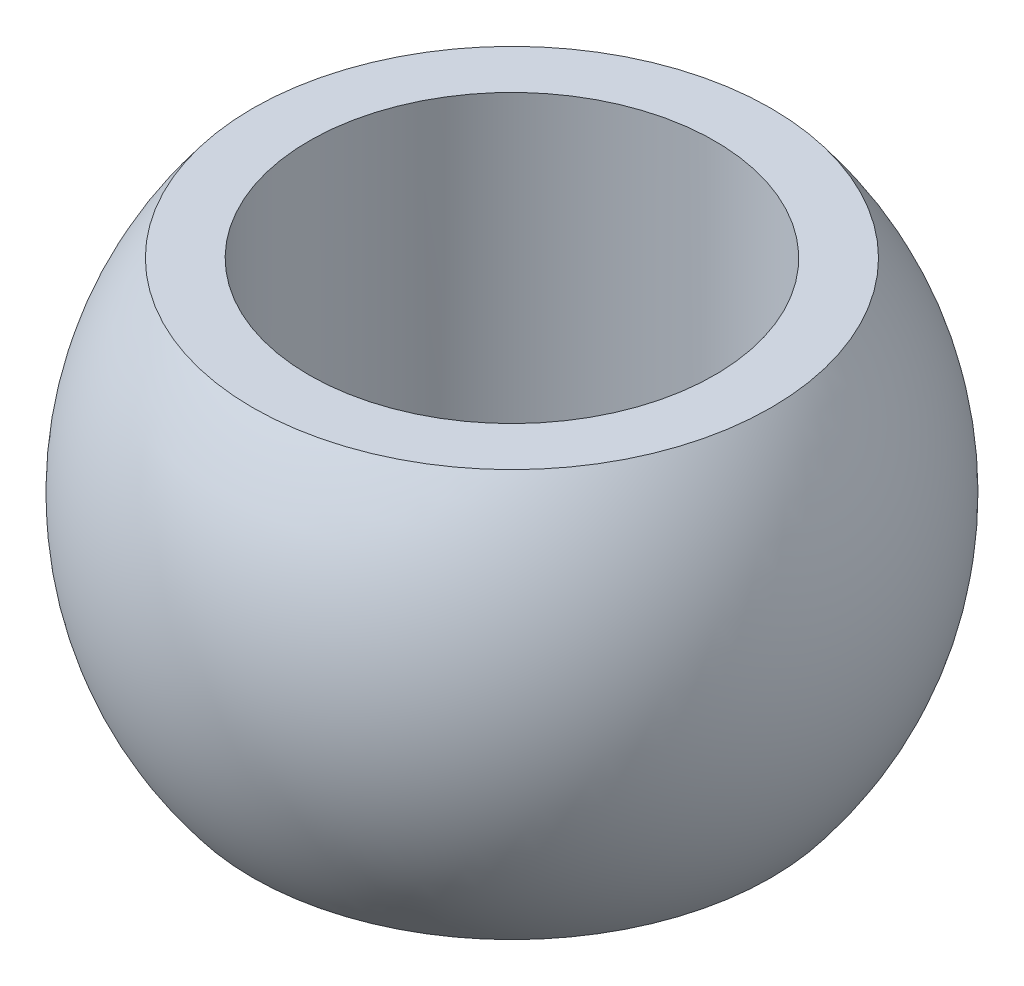
SolidWorks part; units mm, degrees
ref_plane "Front Plane" through (0, 0, 0) normal (0, 0, 1) x (1, 0, 0)
ref_plane "Top Plane" through (0, 0, 0) normal (0, 1, 0) x (1, 0, 0)
ref_plane "Right Plane" through (0, 0, 0) normal (1, 0, 0) x (0, 0, -1)
sketch "Sketch1" plane through (0, 0, 0) normal (0, 0, 1) x (1, 0, 0)
  line L0 (0, 0) -> (0, 9.2303) construction
  line L1 (0, 6.5) -> (0, -6.5)
  arc A0 (0, -6.5) -> (0, 6.5) centre (0, 0) ccw
  dimension "D1" = 13
revolve "Revolve4" add sketch "Sketch1" angle 360 about L0
sketch "Sketch2" plane through (0, 0, 0) normal (0, 1, 0) x (1, 0, 0)
  circle A0 centre (0, 0) radius 4
  dimension "D1" = 8
extrude "Cut-Extrude1" cut sketch "Sketch2" against normal mid plane 19
sketch "Sketch3" plane through (0, 0, 0) normal (0, 0, 1) x (1, 0, 0)
  line L1 (8.4494, 4.0139) -> (-8.4494, 4.0139)
  line L2 (8.4494, 4.0139) -> (8.4494, -4.0139)
  line L3 (8.4494, -4.0139) -> (-8.4494, -4.0139)
  line L4 (-8.4494, 4.0139) -> (-8.4494, -4.0139)
  line L5 (8.4494, 4.0139) -> (-8.4494, -4.0139) construction
  line L6 (8.4494, -4.0139) -> (-8.4494, 4.0139) construction
  point P0 (0, 0)
  dimension "D1" = 8.0279
extrude "Cut-Extrude2" cut sketch "Sketch3" against normal mid plane 19 flip side to cut
